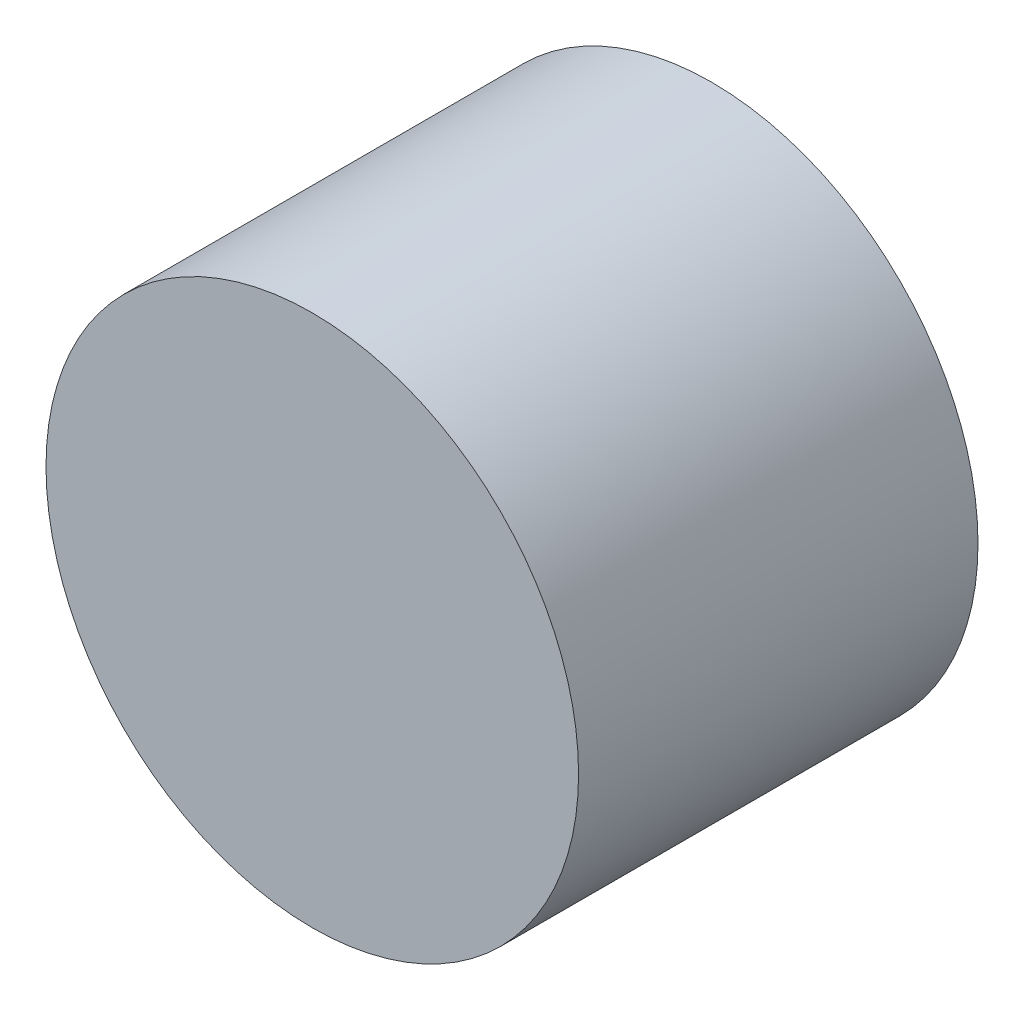
SolidWorks part; units mm, degrees
ref_plane "Front Plane" through (0, 0, 0) normal (0, 0, 1) x (1, 0, 0)
ref_plane "Top Plane" through (0, 0, 0) normal (0, 1, 0) x (1, 0, 0)
ref_plane "Right Plane" through (0, 0, 0) normal (1, 0, 0) x (0, 0, -1)
sketch "Sketch1" plane through (0, 0, 0) normal (0, 0, 1) x (1, 0, 0)
  circle A0 centre (151.7639, -0.2) radius 2.05 construction
  circle A1 centre (151.7639, -0.2) radius 2.05 construction
  circle A2 centre (151.7639, -0.2) radius 2
  dimension "D1" = 4
extrude "Boss-Extrude1" add sketch "Sketch1" against normal blind 3
